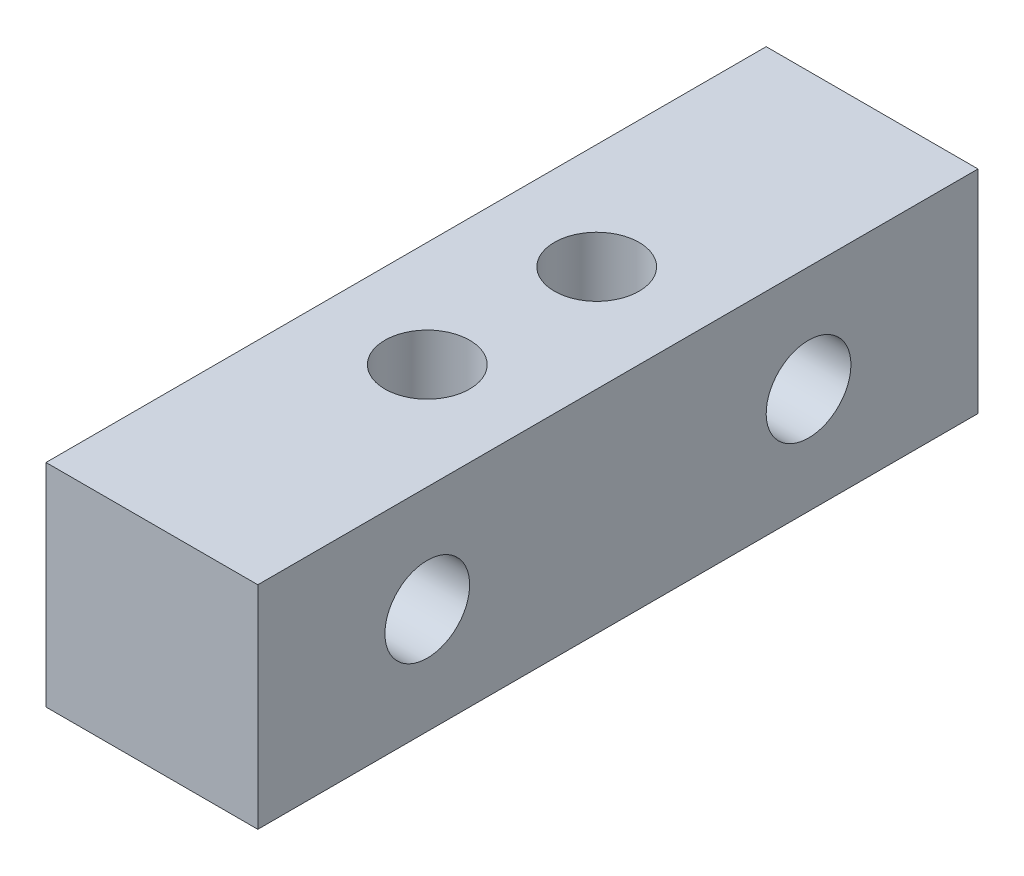
SolidWorks part; units mm, degrees
material "6061 合金"
ref_plane "前视基准面" through (0, 0, 0) normal (0, 0, 1) x (1, 0, 0)
ref_plane "上视基准面" through (0, 0, 0) normal (0, 1, 0) x (1, 0, 0)
ref_plane "右视基准面" through (0, 0, 0) normal (1, 0, 0) x (0, 0, -1)
other "Configuration Table"
sketch "草图1" plane through (0, 0, 0) normal (0, 0, 1) x (1, 0, 0)
  line L1 (0, 0) -> (10, 0)
  line L2 (0, 0) -> (0, -10)
  line L3 (0, -10) -> (10, -10)
  line L4 (10, 0) -> (10, -10)
  dimension "D1" = 10
  dimension "D2" = 10
extrude "凸台-拉伸1" add sketch "草图1" along normal blind 34
sketch "草图2" plane through (10, 0, 0) normal (1, 0, 0) x (0, 0, -1)
  line L0 (-34, -5) -> (0, -5) construction
  line L1 (-34, -10) -> (-34, 0) construction
  line L2 (0, -10) -> (0, 0) construction
  circle A0 centre (-26, -5) radius 2
  circle A1 centre (-8, -5) radius 2
  dimension "D1" = 18
  dimension "D2" = 8
  dimension "D3" = 4
extrude "切除-拉伸1" cut sketch "草图2" against normal through all
sketch "草图3" plane through (0, 0, 0) normal (0, 1, 0) x (1, 0, 0)
  line L0 (5, 0) -> (5, -34) construction
  line L1 (10, 0) -> (0, 0) construction
  line L2 (10, -34) -> (0, -34) construction
  circle A0 centre (5, -13) radius 2
  circle A1 centre (5, -21) radius 2
  dimension "D1" = 4
  dimension "D2" = 8
  dimension "D3" = 13
extrude "切除-拉伸2" cut sketch "草图3" against normal through all
